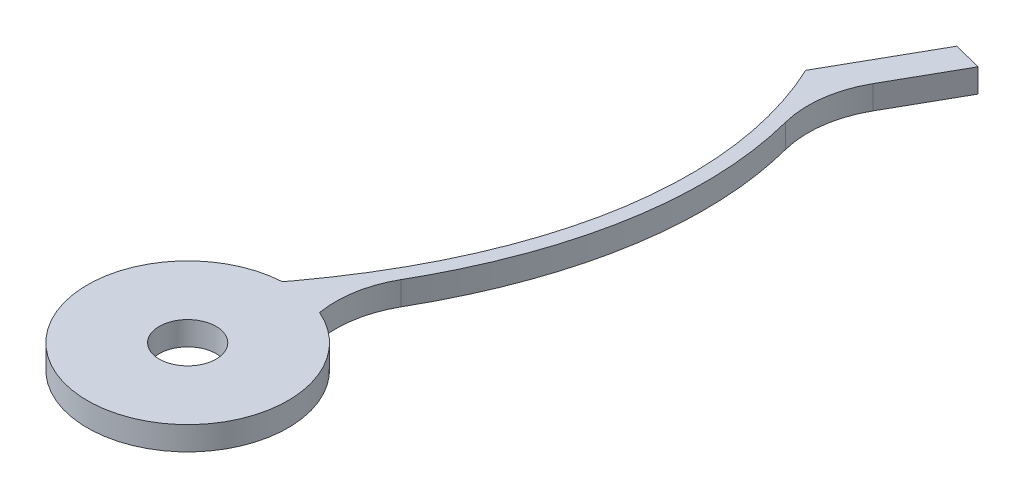
SolidWorks part; units mm, degrees
ref_plane "Front Plane" through (0, 0, 0) normal (0, 0, 1) x (1, 0, 0)
ref_plane "Top Plane" through (0, 0, 0) normal (0, 1, 0) x (1, 0, 0)
ref_plane "Right Plane" through (0, 0, 0) normal (1, 0, 0) x (0, 0, -1)
sketch "Sketch1" plane through (0, 0, 0) normal (0, 1, 0) x (1, 0, 0)
  line L2 (16.5044, 67.0019) -> (13.4976, 67.7801) construction
  line L3 (13.4976, 67.7801) -> (7.7241, 57.5796) construction
  line L6 (16.5044, 67.0019) -> (13.4976, 67.7801)
  line L7 (13.4976, 67.7801) -> (7.7241, 57.5796)
  line L8 (12.4906, 59.9105) -> (16.5044, 67.0019) construction
  line L9 (12.4906, 59.9105) -> (16.5044, 67.0019)
  circle A0 centre (0, 0) radius 3
  arc A1 (-0.6189, 10.5819) -> (4.2084, 9.7288) centre (0, 0) ccw
  arc A4 (-3.8588, 8.1308) -> (-0.0985, 11.2294) centre (-8.1464, 17.165) ccw construction
  arc A7 (-0.6189, 10.5819) -> (-0.0985, 11.2294) centre (-8.1464, 17.165) ccw
  arc A8 (5.4973, 17.0572) -> (8.5861, 2.698) centre (15.0481, 11.5998) ccw construction
  arc A9 (12.4906, 59.9105) -> (11.4151, 51.7335) centre (22.0635, 54.4921) ccw construction
  arc A10 (5.4973, 17.0572) -> (4.2084, 9.7288) centre (15.0481, 11.5998) ccw
  arc A11 (12.4906, 59.9105) -> (11.4151, 51.7335) centre (22.0635, 54.4921) ccw
  spline S1 degree 3 poles (-1782.2375, 2296.677) (267.9955, -2744.423) (1009.4272, 2738.1271) (-2001.0501, -2106.1434) knots -4.89877 -4.89877 -4.89877 -4.89877 5.395841 5.395841 5.395841 5.395841 only from (-0.0985, 11.2294) to (7.7241, 57.5796) construction
  spline S2 degree 3 poles (2448.3569, -1676.941) (-666.5377, 5.089) (-58.9416, -118.1159) (7.9251, 21.7458) (8.2374, 22.4324) (8.8349, 23.8186) (9.1204, 24.5193) (10.4715, 28.0418) (11.3095, 30.9203) (12.0071, 34.6056) (12.1289, 35.347) (12.3355, 36.8392) (12.4204, 37.5916) (12.615, 39.8508) (12.6645, 41.351) (10.3804, 145.584) (-376.1433, 219.735) (-2981.0067, 128.8531) knots -12.662317 -12.662317 -12.662317 -12.662317 0.125 0.125 0.1875 0.1875 0.25 0.25 0.5 0.5 0.5625 0.5625 0.625 0.625 0.75 0.75 9.345681 9.345681 9.345681 9.345681 only from (5.4973, 17.0572) to (11.4151, 51.7335) construction
  spline S3 degree 3 poles (-0.0985, 11.2294) (11.4173, 26.8436) (14.1932, 43.7309) (7.7241, 57.5796) knots 0.117375 0.117375 0.117375 0.117375 0.726154 0.726154 0.726154 0.726154
  spline S4 degree 3 poles (5.4973, 17.0572) (6.2472, 18.3696) (6.9494, 19.705) (7.9251, 21.7458) (8.2374, 22.4324) (8.8349, 23.8186) (9.1204, 24.5193) (10.4715, 28.0418) (11.3095, 30.9203) (12.0071, 34.6056) (12.1289, 35.347) (12.3355, 36.8392) (12.4204, 37.5916) (12.615, 39.8508) (12.6645, 41.351) (12.5663, 45.8332) (12.1758, 48.7971) (11.4151, 51.7335) knots 0 0 0 0 0.125 0.125 0.1875 0.1875 0.25 0.25 0.5 0.5 0.5625 0.5625 0.625 0.625 0.75 0.75 1 1 1 1
  point P6 (3.7115, 9.929)
  dimension "D1" = 6
  dimension "D2" = 21.2
extrude "Boss-Extrude1" add sketch "Sketch1" along normal blind 2.5
